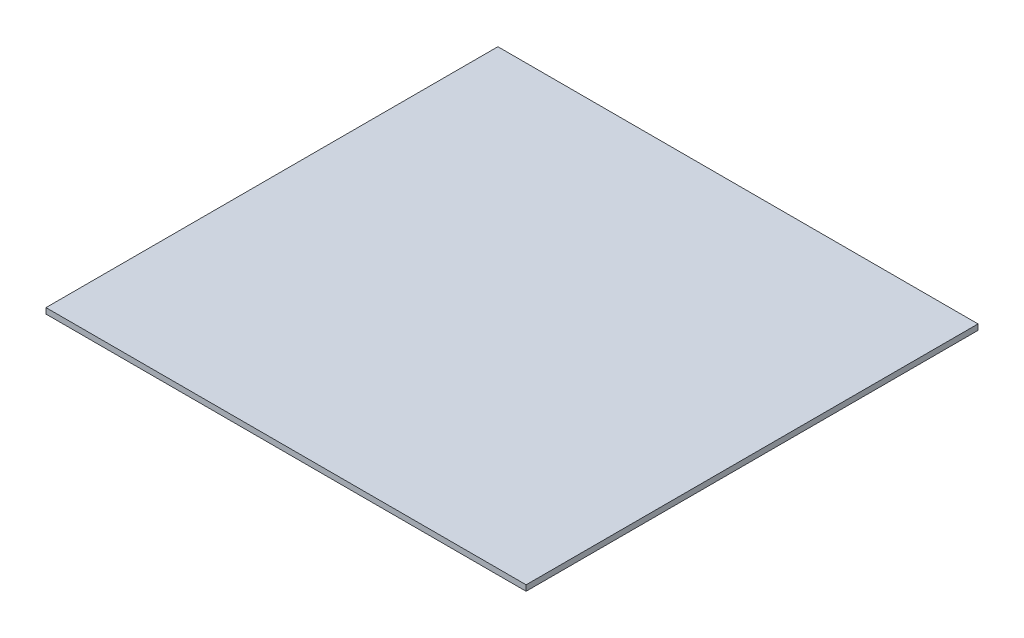
SolidWorks part; units mm, degrees
material "6061 Alloy"
ref_plane "Front Plane" through (0, 0, 0) normal (0, 0, 1) x (1, 0, 0)
ref_plane "Top Plane" through (0, 0, 0) normal (0, 1, 0) x (1, 0, 0)
ref_plane "Right Plane" through (0, 0, 0) normal (1, 0, 0) x (0, 0, -1)
sketch "Sketch1" plane through (0, 0, 0) normal (0, 1, 0) x (1, 0, 0)
  line L1 (-215.9, -203.2) -> (215.9, -203.2)
  line L2 (-215.9, -203.2) -> (-215.9, 203.2)
  line L3 (-215.9, 203.2) -> (215.9, 203.2)
  line L4 (215.9, -203.2) -> (215.9, 203.2)
  line L5 (-215.9, -203.2) -> (215.9, 203.2) construction
  line L6 (-215.9, 203.2) -> (215.9, -203.2) construction
  point P0 (0, 0)
  dimension "D1" = 431.8
  dimension "D2" = 406.4
extrude "Boss-Extrude1" add sketch "Sketch1" along normal blind 5.08
